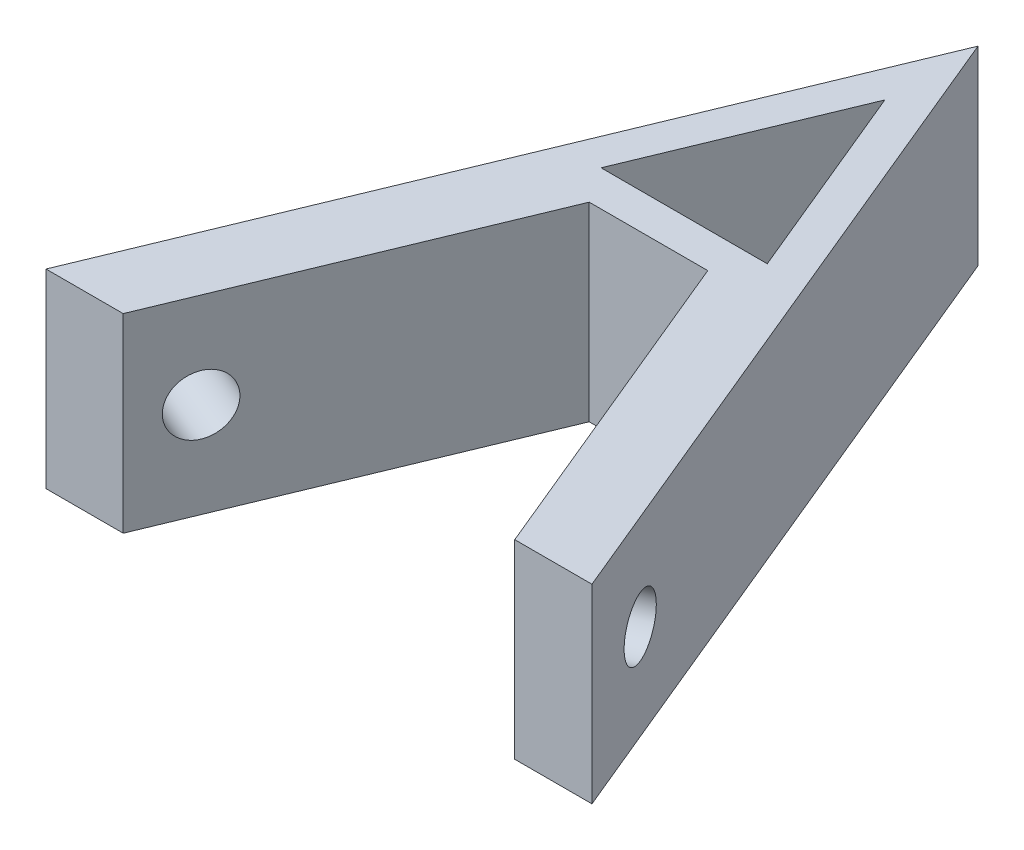
SolidWorks part; units mm, degrees
ref_plane "Front Plane" through (0, 0, 0) normal (0, 0, 1) x (1, 0, 0)
ref_plane "Top Plane" through (0, 0, 0) normal (0, 1, 0) x (1, 0, 0)
ref_plane "Right Plane" through (0, 0, 0) normal (1, 0, 0) x (0, 0, -1)
sketch "Sketch1" plane through (0, 0, 0) normal (0, 1, 0) x (1, 0, 0)
  line L0 (0, 0) -> (-22.961, -55.4328)
  line L1 (-22.961, -55.4328) -> (22.961, -55.4328)
  line L2 (22.961, -55.4328) -> (0, 0)
  point P4 (0, -55.4328)
  dimension "D1" = 45
  dimension "D2" = 60
extrude "Boss-Extrude1" add sketch "Sketch1" along normal blind 16
sketch "Sketch2" plane through (0, 16, 0) normal (0, 1, 0) x (1, 0, 0)
  line L6 (-16.4667, -55.4328) -> (-4.9861, -27.7164)
  line L7 (16.4667, -55.4328) -> (4.9861, -27.7164)
  line L8 (4.9861, -27.7164) -> (-4.9861, -27.7164)
  line L9 (-22.961, -55.4328) -> (22.961, -55.4328) construction
  line L10 (0, 0) -> (-22.961, -55.4328) construction
  line L11 (22.961, -55.4328) -> (0, 0) construction
  line L12 (-6.9907, -24.7164) -> (6.9907, -24.7164)
  line L13 (6.9907, -24.7164) -> (0, -7.8394)
  line L14 (0, -7.8394) -> (-6.9907, -24.7164)
  line L15 (-16.4667, -55.4328) -> (16.4667, -55.4328)
  dimension "D1" = 6
  dimension "D2" = 6
  dimension "D3" = 3
  dimension "30" = 30
  dimension "D4" = 3
extrude "Cut-Extrude1" cut sketch "Sketch2" against normal blind 16
sketch "Sketch3" plane through (0, 0, 0) normal (0.9239, 0, -0.3827) x (-0.3827, 0, -0.9239)
  line L0 (-60, 8) -> (0, 8) construction
  line L1 (-60, 16) -> (-60, 0) construction
  line L2 (0, 16) -> (0, 0) construction
  circle A0 centre (-52.5, 8) radius 2.5
  dimension "D1" = 5
  dimension "D2" = 7.5
sketch "Sketch4" plane through (0, 0, 0) normal (-0.9239, 0, -0.3827) x (-0.3827, 0, 0.9239)
  line L0 (0, 8) -> (60, 8) construction
  line L3 (60, 16) -> (60, 0) construction
  line L4 (0, 16) -> (0, 0) construction
  circle A0 centre (52.5, 8) radius 2.5
  dimension "D1" = 5
  dimension "D2" = 7.5
extrude "Cut-Extrude2" cut sketch "Sketch3" against normal blind 16
extrude "Cut-Extrude3" cut sketch "Sketch4" against normal blind 16
